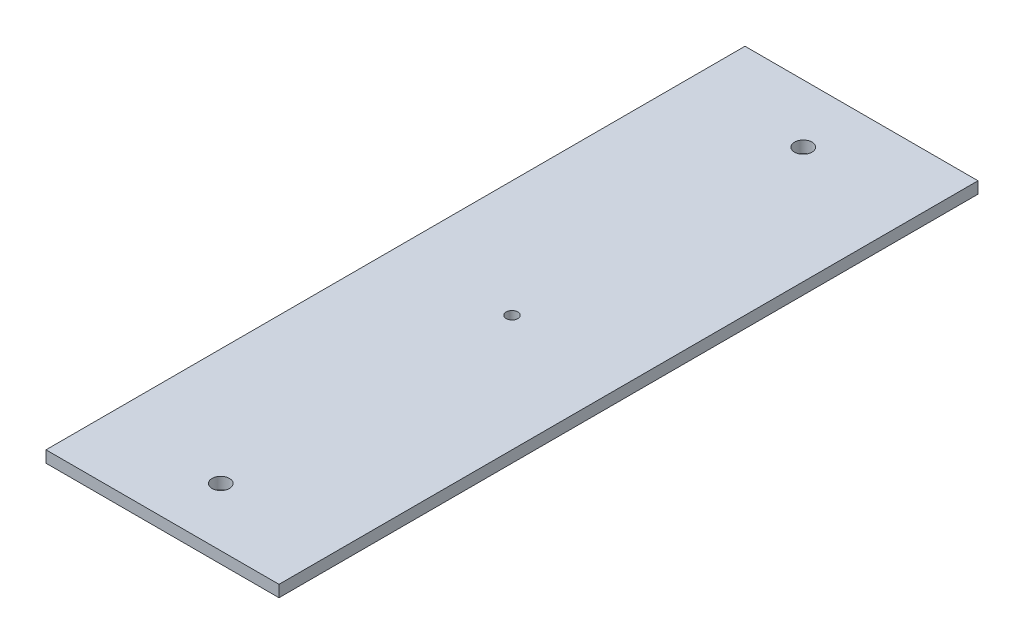
SolidWorks part; units mm, degrees
ref_plane "Front Plane" through (0, 0, 0) normal (0, 0, 1) x (1, 0, 0)
ref_plane "Top Plane" through (0, 0, 0) normal (0, 1, 0) x (1, 0, 0)
ref_plane "Right Plane" through (0, 0, 0) normal (1, 0, 0) x (0, 0, -1)
sketch "Sketch1" plane through (0, 0, 0) normal (0, 1, 0) x (1, 0, 0)
  line L1 (0, 0) -> (40, 0)
  line L2 (0, 0) -> (0, 120)
  line L3 (0, 120) -> (40, 120)
  line L4 (40, 0) -> (40, 120)
  circle A0 centre (20, 10) radius 1.5
  circle A1 centre (20, 110) radius 1.5
  circle A2 centre (20, 60) radius 1
  point P9 (20, 120)
  dimension "D3" = 10
  dimension "D4" = 10
  dimension "D6" = 20
  dimension "D7" = 60
  dimension "D8" = 2
  dimension "D1" = 40
  dimension "D2" = 120
  dimension "D5" = 20
extrude "Boss-Extrude1" add sketch "Sketch1" along normal blind 2
